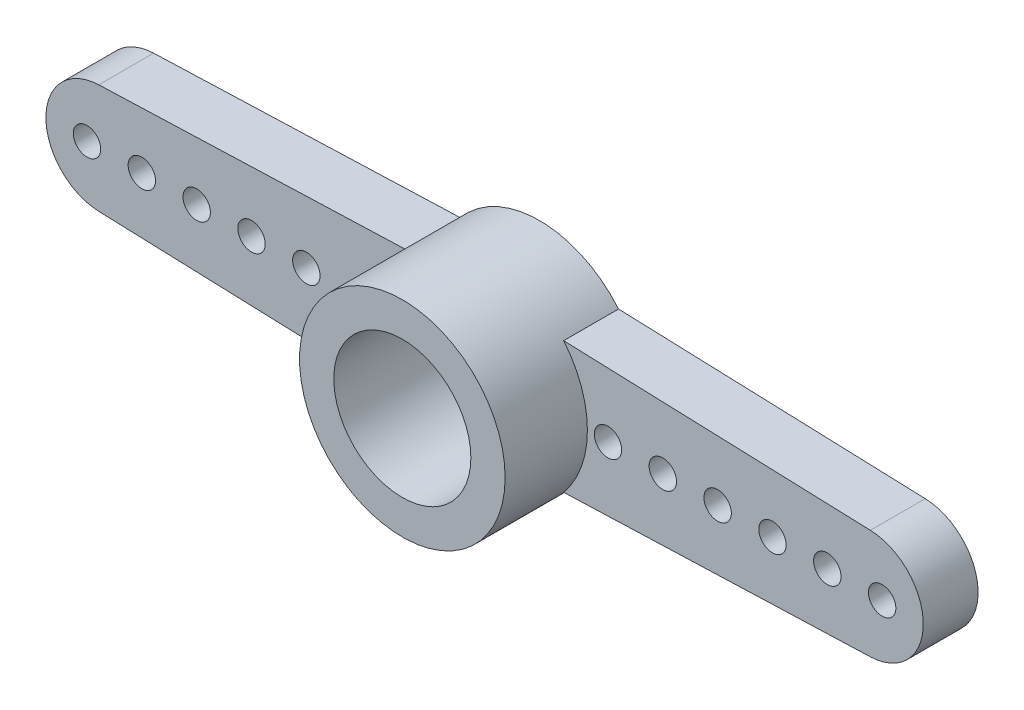
SolidWorks part; units mm, degrees
ref_plane "Спереди" through (0, 0, 0) normal (0, 0, 1) x (1, 0, 0)
ref_plane "Сверху" through (0, 0, 0) normal (0, 1, 0) x (1, 0, 0)
ref_plane "Справа" through (0, 0, 0) normal (1, 0, 0) x (0, 0, -1)
sketch "Эскиз1" plane through (0, 0, 0) normal (0, 0, 1) x (1, 0, 0)
  line L0 (0, 0) -> (-14, 0)
  line L1 (-14.0708, 1.9987) -> (0, 2.4974)
  line L2 (-14.0708, -1.9987) -> (0, -2.4974)
  line L4 (14.0708, -1.9987) -> (0, -2.4974)
  line L5 (14.0708, 1.9987) -> (0, 2.4974)
  circle A0 centre (0, 0) radius 3.75
  circle A1 centre (0, 0) radius 2.5
  arc A2 (-13.967, -1.9997) -> (-14.0708, 1.9987) centre (-14, 0) cw
  arc A3 (13.967, -1.9997) -> (14.0708, 1.9987) centre (14, 0) ccw
  dimension "D1" = 7.5
  dimension "D2" = 5
  dimension "D4" = 2
  dimension "D3" = 14
extrude "Бобышка-Вытянуть3" add sketch "Эскиз1" along normal blind 2
sketch "Эскиз2" plane through (0, 0, 2) normal (0, 0, 1) x (1, 0, 0)
  circle A0 centre (0, 0) radius 3.75
  circle A1 centre (0, 0) radius 2.5
  dimension "D1" = 5
extrude "Бобышка-Вытянуть5" add sketch "Эскиз2" along normal blind 3 separate body
sketch "Эскиз3" plane through (0, 0, 2) normal (0, 0, -1) x (-1, 0, 0)
  circle A0 centre (0, 0) radius 3.75
  circle A1 centre (0, 0) radius 2.5
extrude "Бобышка-Вытянуть6" add sketch "Эскиз3" along normal blind 2
sketch "Эскиз4" plane through (0, 0, 0) normal (0, 0, -1) x (-1, 0, 0)
  line L0 (-16, 0) -> (-14.5, 0)
  line L1 (-14.5, 0) -> (-12.5, 0)
  line L2 (-12.5, 0) -> (-10.5, 0)
  line L3 (-10.5, 0) -> (-8.5, 0)
  line L4 (-8.5, 0) -> (-6.5, 0)
  line L5 (-6.5, 0) -> (-4.5, 0)
  arc A0 (-14.0708, 1.9987) -> (-14.0708, -1.9987) centre (-14, 0) ccw construction
  circle A1 centre (-14.5, 0) radius 0.5
  circle A2 centre (-12.5, 0) radius 0.5
  circle A3 centre (-10.5, 0) radius 0.5
  circle A4 centre (-8.5, 0) radius 0.5
  circle A5 centre (-6.5, 0) radius 0.5
  circle A6 centre (-4.5, 0) radius 0.5
  circle A7 centre (4.5, 0) radius 0.5
  circle A8 centre (6.5, 0) radius 0.5
  circle A9 centre (8.5, 0) radius 0.5
  circle A10 centre (10.5, 0) radius 0.5
  circle A11 centre (12.5, 0) radius 0.5
  circle A12 centre (14.5, 0) radius 0.5
  dimension "D2" = 1
  dimension "D8" = 1
  dimension "D9" = 1
  dimension "D10" = 1
  dimension "D11" = 1
  dimension "D12" = 1
  dimension "D1" = 1.5
  dimension "D3" = 2
  dimension "D4" = 2
  dimension "D5" = 2
  dimension "D6" = 2
  dimension "D7" = 2
extrude "Вырез-Вытянуть1" cut sketch "Эскиз4" against normal blind 2
sketch "Эскиз5" plane through (0, 0, 0) normal (0, 0, -1) x (-1, 0, 0)
  circle A0 centre (0, 0) radius 2.5
extrude "Бобышка-Вытянуть7" add sketch "Эскиз5" against normal blind 1
sketch "Эскиз6" plane through (0, 0, 0) normal (0, 0, -1) x (-1, 0, 0)
  circle A0 centre (0, 0) radius 2.5
  dimension "D1" = 5
extrude "Вырез-Вытянуть2" cut sketch "Эскиз6" against normal blind 0.5
sketch "Эскиз7" plane through (0, 0, 0.5) normal (0, 0, -1) x (-1, 0, 0)
  circle A0 centre (0, 0) radius 1.25
  dimension "D1" = 2.5
extrude "Вырез-Вытянуть3" cut sketch "Эскиз7" against normal blind 5
sketch "Sketch2" plane through (0, 0, 0) normal (0, 0, -1) x (-1, 0, 0)
  line L0 (-8.5, 0) -> (0, 0)
  line L1 (0, 0) -> (8.5, 0)
